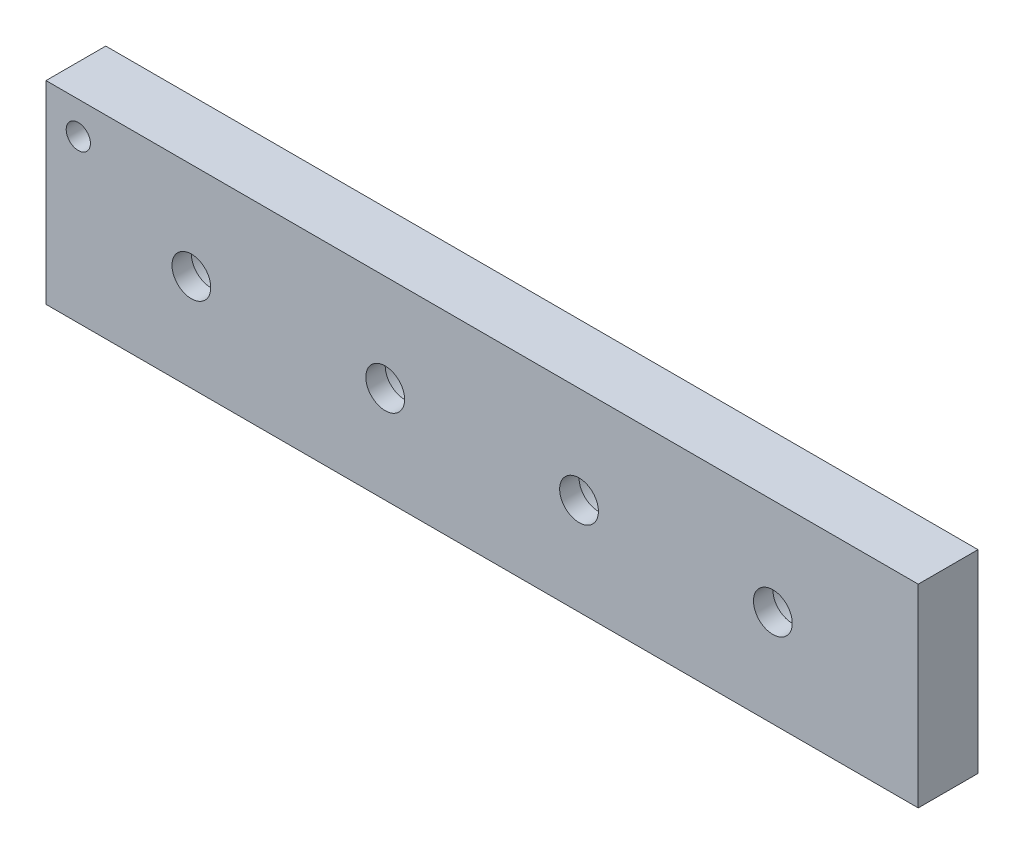
SolidWorks part; units mm, degrees
ref_plane "Front Plane" through (0, 0, 0) normal (0, 0, 1) x (1, 0, 0)
ref_plane "Top Plane" through (0, 0, 0) normal (0, 1, 0) x (1, 0, 0)
ref_plane "Right Plane" through (0, 0, 0) normal (1, 0, 0) x (0, 0, -1)
sketch "Coupon_bar_54x12x3p7_profile" plane through (0, 0, 0) normal (0, 0, 1) x (1, 0, 0)
  line L1 (-27, -6) -> (27, -6)
  line L2 (-27, -6) -> (-27, 6)
  line L3 (-27, 6) -> (27, 6)
  line L4 (27, -6) -> (27, 6)
  dimension "D1" = 54
  dimension "D2" = 12
  dimension "D3" = 27
  dimension "D4" = 6
extrude "Coupon_bar_54x12x3p7" add sketch "Coupon_bar_54x12x3p7_profile" along normal blind 3.7
sketch "Press_sockets_4p65_4p75_4p85_4p95_depth2p5_profile" plane through (0, 0, 0) normal (0, 0, 1) x (1, 0, 0)
  circle A0 centre (-18, 0) radius 2.325
  circle A1 centre (-6, 0) radius 2.375
  circle A2 centre (6, 0) radius 2.425
  circle A3 centre (18, 0) radius 2.475
  dimension "D1" = 4.65
  dimension "D2" = 4.75
  dimension "D3" = 4.85
  dimension "D4" = 4.95
  dimension "D5" = 6
  dimension "D6" = 18
  dimension "D7" = 6
  dimension "D8" = 18
extrude "Press_sockets_4p65_4p75_4p85_4p95_depth2p5" cut sketch "Press_sockets_4p65_4p75_4p85_4p95_depth2p5_profile" along normal blind 2.5
sketch "M2_centre_screw_clearance_profile" plane through (0, 0, 0) normal (0, 0, 1) x (1, 0, 0)
  circle A0 centre (-18, 0) radius 1.2
  circle A1 centre (-6, 0) radius 1.2
  circle A2 centre (6, 0) radius 1.2
  circle A3 centre (18, 0) radius 1.2
  dimension "D1" = 2.4
  dimension "D2" = 2.4
  dimension "D3" = 2.4
  dimension "D4" = 2.4
  dimension "D5" = 6
  dimension "D6" = 18
  dimension "D7" = 6
  dimension "D8" = 18
extrude "M2_centre_screw_clearance" cut sketch "M2_centre_screw_clearance_profile" along normal through all from offset 50
sketch "Orientation_mark_at_smallest_socket_profile" plane through (0, 0, 0) normal (0, 0, 1) x (1, 0, 0)
  circle A0 centre (-25, 4) radius 0.75
  dimension "D1" = 1.5
  dimension "D2" = 25
  dimension "D3" = 4
extrude "Orientation_mark_at_smallest_socket" cut sketch "Orientation_mark_at_smallest_socket_profile" along normal through all from offset 50
